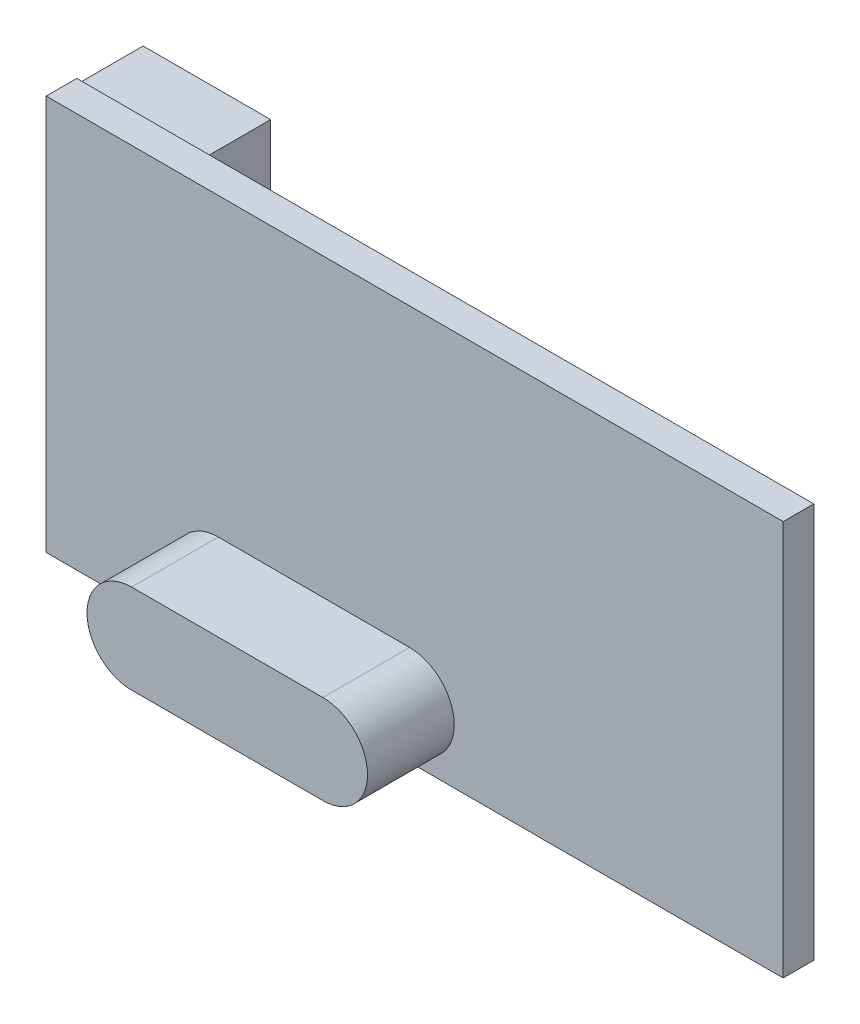
SolidWorks part; units mm, degrees
ref_plane "Front Plane" through (0, 0, 0) normal (0, 0, 1) x (1, 0, 0)
ref_plane "Top Plane" through (0, 0, 0) normal (0, 1, 0) x (1, 0, 0)
ref_plane "Right Plane" through (0, 0, 0) normal (1, 0, 0) x (0, 0, -1)
sketch "Sketch1" plane through (0, 0, 0) normal (0, 0, 1) x (1, 0, 0)
  line L0 (14.45, 7.75) -> (-14.45, -7.75) construction
  line L1 (-14.45, 7.75) -> (14.45, 7.75)
  line L2 (-14.45, 7.75) -> (-14.45, -7.75)
  line L3 (-14.45, -7.75) -> (14.45, -7.75)
  line L4 (14.45, 7.75) -> (14.45, -7.75)
  point P4 (0, 0)
  dimension "D1" = 28.9
  dimension "D2" = 15.5
extrude "Boss-Extrude1" add sketch "Sketch1" along normal blind 1.2 contours L1 L2 L0 | L4 L0 L3
sketch "Sketch2" plane through (0, 0, 1.2) normal (0, 0, 1) x (1, 0, 0)
  line L0 (-14.45, 7.75) -> (-14.45, -7.75) construction
  line L1 (-7.7, -3.85) -> (-0.2, -3.85)
  line L2 (-7.7, -3.85) -> (-7.7, -7.35) construction
  line L3 (-7.7, -7.35) -> (-0.2, -7.35)
  line L4 (-0.2, -3.85) -> (-0.2, -7.35) construction
  line L5 (-14.45, -7.75) -> (14.45, -7.75) construction
  arc A0 (-7.7, -3.85) -> (-7.7, -7.35) centre (-7.7, -5.6) ccw
  arc A1 (-0.2, -3.85) -> (-0.2, -7.35) centre (-0.2, -5.6) cw
  dimension "D1" = 11
  dimension "D2" = 3.5
  dimension "D3" = 5
  dimension "D4" = 0.4
extrude "Boss-Extrude2" add sketch "Sketch2" along normal blind 3.4
sketch "Sketch3" plane through (0, 0, 0) normal (0, 0, -1) x (-1, 0, 0)
  line L0 (14.45, 7.75) -> (14.45, -7.75) construction
  line L1 (14.35, 7.65) -> (9.35, 7.65)
  line L2 (14.35, 7.65) -> (14.35, -2.35)
  line L3 (14.35, -2.35) -> (9.35, -2.35)
  line L4 (9.35, 7.65) -> (9.35, -2.35)
  line L5 (14.45, 7.75) -> (-14.45, 7.75) construction
  dimension "D1" = 10
  dimension "D2" = 5
  dimension "D3" = 0.1
  dimension "D4" = 0.1
extrude "Boss-Extrude3" add sketch "Sketch3" along normal blind 2.5
